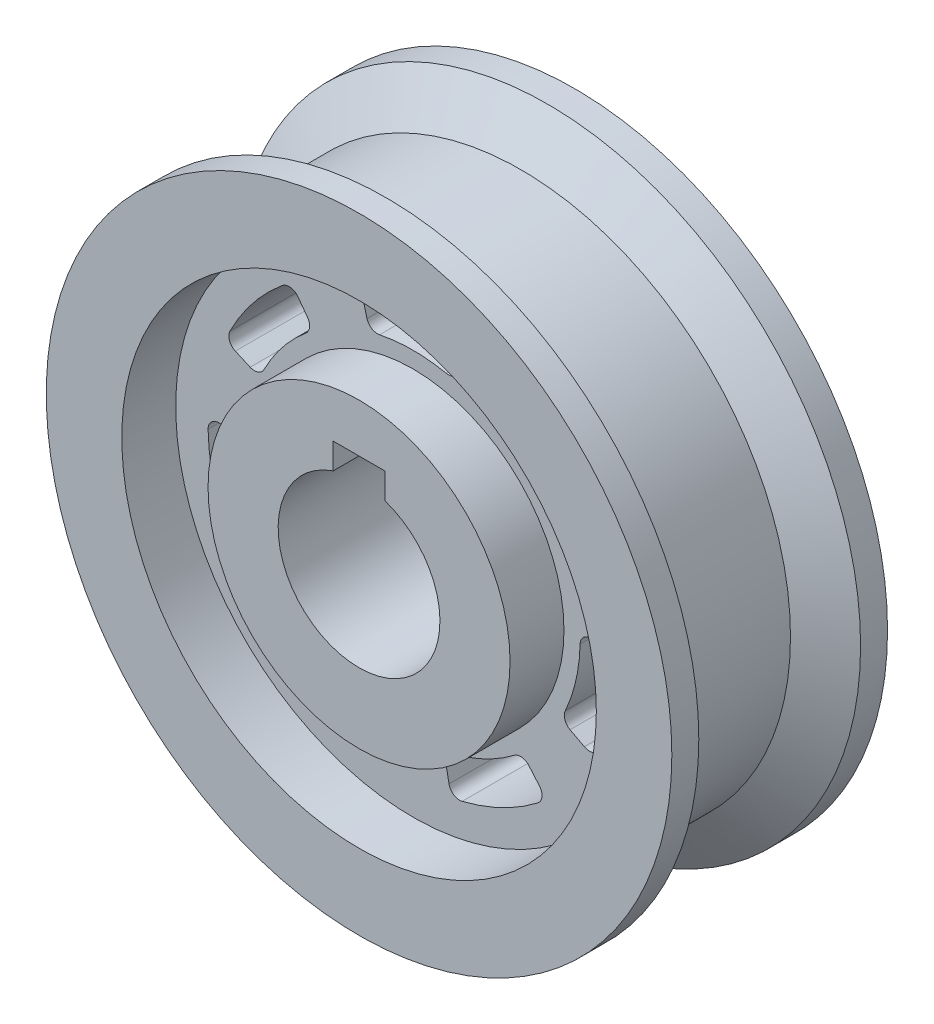
SolidWorks part; units mm, degrees
ref_plane "Front Plane" through (0, 0, 0) normal (0, 0, 1) x (1, 0, 0)
ref_plane "Top Plane" through (0, 0, 0) normal (0, 1, 0) x (1, 0, 0)
ref_plane "Right Plane" through (0, 0, 0) normal (1, 0, 0) x (0, 0, -1)
sketch "Sketch2" plane through (0, 0, 0) normal (1, 0, 0) x (0, 0, -1)
  line L0 (-12.7, 0) -> (0, 0) construction
  line L1 (0, 0) -> (12.7, 0) construction
  line L10 (0, 0) -> (0, 31.75) construction
  line L11 (12.7, 0) -> (12.7, 17.78)
  line L12 (12.7, 17.78) -> (6.35, 17.78)
  line L13 (6.35, 17.78) -> (6.35, 27.94)
  line L14 (6.35, 27.94) -> (12.7, 27.94)
  line L15 (12.7, 27.94) -> (12.7, 36.83)
  line L16 (12.7, 36.83) -> (9.525, 36.83)
  line L17 (9.525, 36.83) -> (6.35, 31.75)
  line L18 (6.35, 31.75) -> (-6.35, 31.75)
  line L19 (-9.525, 36.83) -> (-6.35, 31.75)
  line L20 (-12.7, 36.83) -> (-9.525, 36.83)
  line L21 (-12.7, 27.94) -> (-12.7, 36.83)
  line L22 (-6.35, 27.94) -> (-12.7, 27.94)
  line L23 (-6.35, 17.78) -> (-6.35, 27.94)
  line L24 (-12.7, 17.78) -> (-6.35, 17.78)
  line L25 (-12.7, 0) -> (-12.7, 17.78)
  line L26 (12.7, 0) -> (-12.7, 0)
  point P2 (9.525, 27.94)
  point P15 (0, 31.75)
  dimension "D1" = 31.75
  dimension "D2" = 12.7
  dimension "D3" = 12.7
  dimension "D4" = 17.78
  dimension "D5" = 10.16
  dimension "D6" = 12.7
  dimension "D7" = 6.35
  dimension "D8" = 8.89
  dimension "D9" = 3.175
  dimension "D10" = 12.7
  dimension "D11" = 3.81
  dimension "D12" = 6.35
revolve "Revolve3" add sketch "Sketch2" angle 360 about L1
sketch "Sketch3" plane through (0, 0, 12.7) normal (0, 0, 1) x (1, 0, 0)
  line L0 (0, 0) -> (0, 12.065) construction
  line L1 (-3.048, 12.065) -> (3.048, 12.065)
  line L2 (3.048, 12.065) -> (3.048, 9.0242)
  line L3 (-3.048, 12.065) -> (-3.048, 9.0242)
  arc A0 (-3.048, 9.0242) -> (3.048, 9.0242) centre (0, 0) ccw
  dimension "D1" = 19.05
  dimension "D2" = 12.065
  dimension "D3" = 3.048
extrude "Cut-Extrude1" cut sketch "Sketch3" against normal through all and the other way through all
sketch "Sketch4" plane through (0, 0, 6.35) normal (0, 0, 1) x (1, 0, 0)
  line L0 (0, 0) -> (0, 27.94) construction
  line L1 (0, 0) -> (7.2314, 26.988) construction
  line L2 (-5.9075, 22.047) -> (-5.4136, 20.2038)
  line L3 (5.9075, 22.047) -> (5.4136, 20.2038)
  circle A0 centre (0, 0) radius 27.94 construction
  arc A1 (4.9408, 23.6188) -> (-4.9408, 23.6188) centre (0, 0) ccw
  arc A2 (3.9331, 19.2881) -> (-3.9331, 19.2881) centre (0, 0) ccw
  arc A3 (5.9075, 22.047) -> (4.9408, 23.6188) centre (4.6807, 22.3757) ccw
  arc A4 (5.4136, 20.2038) -> (3.9331, 19.2881) centre (4.1869, 20.5325) cw
  arc A5 (-5.4136, 20.2038) -> (-3.9331, 19.2881) centre (-4.1869, 20.5325) ccw
  arc A6 (-5.9075, 22.047) -> (-4.9408, 23.6188) centre (-4.6807, 22.3757) cw
  point P14 (6.2453, 23.3078)
  point P17 (5.0949, 19.0142)
  point P20 (-5.0949, 19.0142)
  point P23 (-6.2453, 23.3078)
  dimension "D2" = 24.13
  dimension "D3" = 1.27
  dimension "D1" = 15
  dimension "D4" = 4.2935
extrude "Cut-Extrude2" cut sketch "Sketch4" against normal through all
pattern_circular "CirPattern1" count 7 over 360 about axis through (0, 0, 0) along (0, 0, 1) of "Cut-Extrude2"
